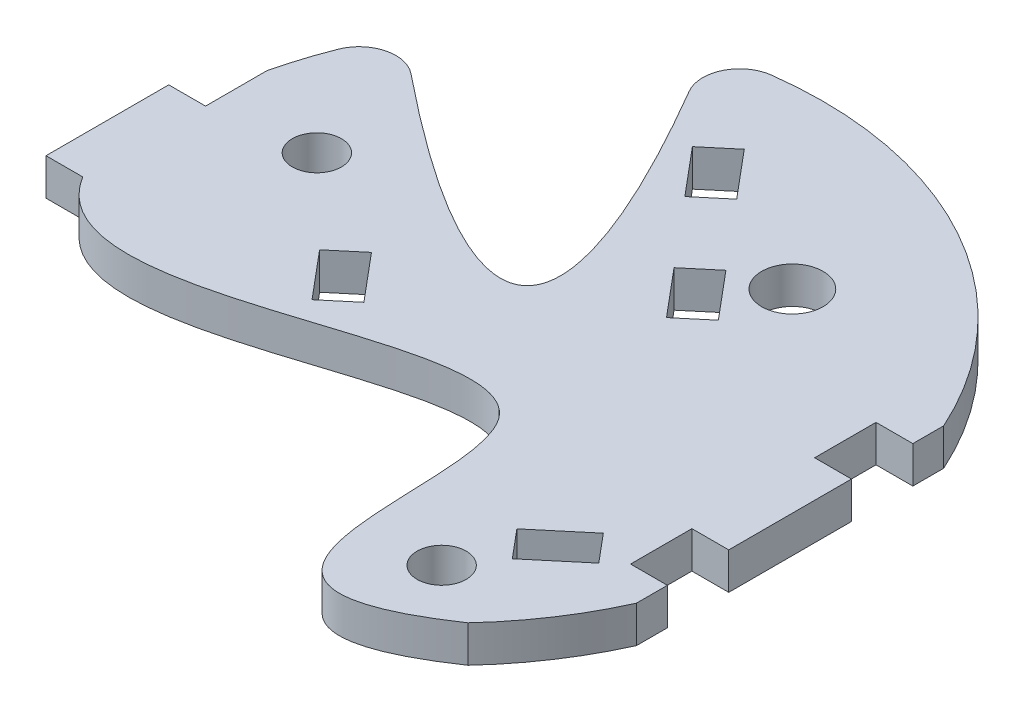
SolidWorks part; units mm, degrees
ref_plane "Alzado" through (0, 0, 0) normal (0, 0, 1) x (1, 0, 0)
ref_plane "Planta" through (0, 0, 0) normal (0, 1, 0) x (1, 0, 0)
ref_plane "Vista lateral" through (0, 0, 0) normal (1, 0, 0) x (0, 0, -1)
sketch "Croquis1" plane through (0, 0, 0) normal (0, 1, 0) x (1, 0, 0)
  circle A0 centre (0, 0) radius 30.5
extrude "Saliente-Extruir1" add sketch "Croquis1" along normal blind 3
sketch "Croquis5" plane through (0, 3, 0) normal (0, 1, 0) x (1, 0, 0)
  line L0 (0, 0) -> (0, 10)
  line L1 (28.8141, -5) -> (30.0874, -5)
  line L2 (28.8141, 5) -> (30.0874, 5)
  line L3 (-24.8141, 10) -> (-28.8141, 10)
  line L4 (24.8141, -5) -> (24.8141, -10)
  line L5 (-24.8141, -10) -> (-28.8141, -10)
  line L6 (24.8141, -5) -> (28.8141, -5)
  line L7 (24.8141, 5) -> (24.8141, 10)
  line L8 (-24.8141, 5) -> (-28.8141, 5)
  line L9 (-24.8141, 5) -> (-24.8141, 10)
  line L10 (-24.8141, -5) -> (-28.8141, -5)
  line L11 (-24.8141, -5) -> (-24.8141, -10)
  line L12 (24.8141, 5) -> (28.8141, 5)
  line L13 (24.8141, -10) -> (28.8141, -10)
  line L14 (24.8141, 10) -> (28.8141, 10)
  line L15 (-28.8141, 5) -> (-30.0874, 5)
  line L16 (-28.8141, -5) -> (-30.0874, -5)
  circle A1 centre (0, 0) radius 30.5 construction
  arc A2 (-28.8141, 10) -> (-30.0874, 5) centre (0, 0) ccw
  arc A3 (28.8141, 10) -> (28.8141, -10) centre (0, 0) cw
  arc A4 (-30.0874, -5) -> (-28.8141, -10) centre (0, 0) ccw
  arc A5 (30.0874, -5) -> (28.8141, -10) centre (0, 0) cw
  arc A6 (28.8141, 10) -> (30.0874, 5) centre (0, 0) cw
extrude "Cortar-Extruir3" cut sketch "Croquis5" against normal blind 4
sketch "Croquis9" plane through (0, 3, 0) normal (0, 1, 0) x (1, 0, 0)
  line L0 (7.2803, 10.7703) -> (22.8679, -7.8063)
  line L1 (-8.3073, 29.3469) -> (7.2803, 10.7703)
  line L2 (7.9714, 14.6138) -> (11.1854, 10.7835)
  line L3 (-24.8141, -5) -> (-24.8141, -10)
  line L4 (-24.8141, -10) -> (-28.8141, -10)
  line L5 (11.1854, 10.7835) -> (8.8872, 8.8552)
  line L6 (-7.7325, 1.4366) -> (-10.0306, -0.4918)
  line L7 (7.9714, 14.6138) -> (5.6733, 12.6854)
  line L8 (-10.0306, -0.4918) -> (-6.8167, -4.322)
  line L9 (-6.8167, -4.322) -> (-4.5186, -2.3936)
  line L10 (21.5273, -8.9312) -> (23.4556, -11.2293)
  line L11 (-2.1205, 21.9737) -> (1.0934, 18.1435)
  line L12 (0.1776, 23.902) -> (3.3916, 20.0718)
  line L13 (-24.8141, 10) -> (-28.8141, 10)
  line L14 (3.3916, 20.0718) -> (1.0934, 18.1435)
  line L15 (0.1776, 23.902) -> (-2.1205, 21.9737)
  line L20 (-7.7325, 1.4366) -> (-4.5186, -2.3936)
  line L21 (17.6971, -12.1451) -> (19.6254, -14.4432)
  line L23 (19.6254, -14.4432) -> (23.4556, -11.2293)
  line L27 (17.6971, -12.1451) -> (21.5273, -8.9312)
  arc A1 (28.8141, 10) -> (-28.8141, 10) centre (0, 0) ccw construction
  circle A4 centre (-16.9835, 6.2386) radius 2
  arc A5 (-28.8141, -10) -> (28.8141, -10) centre (0, 0) ccw construction
  arc A6 (-23.4189, 14.4323) -> (-18.7453, 15.6646) centre (-20.6289, 13.3296) cw
  arc A7 (-28.8141, -10) -> (22.3289, -20.7766) centre (0, 0) ccw
  arc A8 (-28.8141, 10) -> (-8.3073, 29.3469) centre (0, 0) cw
  circle A9 centre (17.204, -17.7804) radius 2
  spline S0 degree 3 poles (22.3289, -20.7766) (5.9738, -31.8512) (22.1768, 15.8352) (-18.2069, -15.8076) (-24.8141, -5) knots 0 0 0 0 0.44579 1 1 1 1
  spline S1 degree 3 poles (-24.8141, -5) (-26.3603, 1.5896) (-25.8363, 8.3159) (-23.4189, 14.4323) knots 0 0 0 0 0.831813 0.831813 0.831813 0.831813
  spline S2 degree 3 poles (-18.7453, 15.6646) (3.867, -2.5765) (8.0942, 2.4964) (-8.3073, 29.3469) knots 0.040528 0.040528 0.040528 0.040528 1 1 1 1
  dimension "D1" = 3
extrude "Cortar-Extruir6" cut sketch "Croquis9" against normal blind 10
fillet "Redondeo1" radius 3 1 edges at (-8.3073, 1.5, -29.3469)
sketch "Croquis10" plane through (0, 3, 0) normal (0, 1, 0) x (1, 0, 0)
  line L0 (0, 0) -> (12, 0)
  line L1 (12, 0) -> (12, 16)
  circle A0 centre (12, 16) radius 2.5
extrude "Cortar-Extruir7" cut sketch "Croquis10" against normal blind 10
sketch "Croquis11" plane through (0, 3, 0) normal (0, 1, 0) x (1, 0, 0)
  line L0 (-24.8141, 5) -> (-27.8141, 5)
  line L1 (-27.8141, 5) -> (-27.8141, -5)
  line L2 (-24.8141, -5) -> (-30.0874, -5) construction
  line L3 (24.8141, 5) -> (27.8141, 5)
  line L4 (24.8141, 5) -> (30.0874, 5) construction
  line L5 (27.8141, 5) -> (27.8141, -5)
  line L6 (24.8141, -5) -> (30.0874, -5) construction
  line L7 (24.8141, 10) -> (27.8141, 10)
  line L8 (24.8141, 10) -> (28.8141, 10) construction
  line L9 (27.8141, 10) -> (27.8141, 12.5151)
  line L10 (24.8141, -10) -> (27.8141, -10)
  line L11 (24.8141, -10) -> (28.8141, -10) construction
  line L12 (27.8141, -10) -> (27.8141, -12.5151)
  arc A0 (28.8141, 10) -> (-3.9586, 30.242) centre (0, 0) ccw construction
  arc A1 (22.3289, -20.7766) -> (28.8141, -10) centre (0, 0) ccw construction
  arc M11 (28.8141, 10) -> (-3.9586, 30.242) centre (0, 0) ccw
  line M17 (-24.8141, 5) -> (-30.0874, 5)
  arc M18 (-30.0874, 5) -> (-30.0874, -5) centre (0, 0) ccw
  line M19 (-30.0874, -5) -> (-24.8141, -5)
  arc M21 (22.3289, -20.7766) -> (28.8141, -10) centre (0, 0) ccw
  line M22 (28.8141, -10) -> (24.8141, -10)
  line M24 (24.8141, -5) -> (30.0874, -5)
  arc M25 (30.0874, -5) -> (30.0874, 5) centre (0, 0) ccw
  line M26 (30.0874, 5) -> (24.8141, 5)
  line M28 (24.8141, 10) -> (28.8141, 10)
extrude "Cortar-Extruir8" cut sketch "Croquis11" against normal through all and the other way through all contours L5 M26 M24 M25 | L12 M22 M21 | L9 M28 M11 | L1 M17 M18 M19
